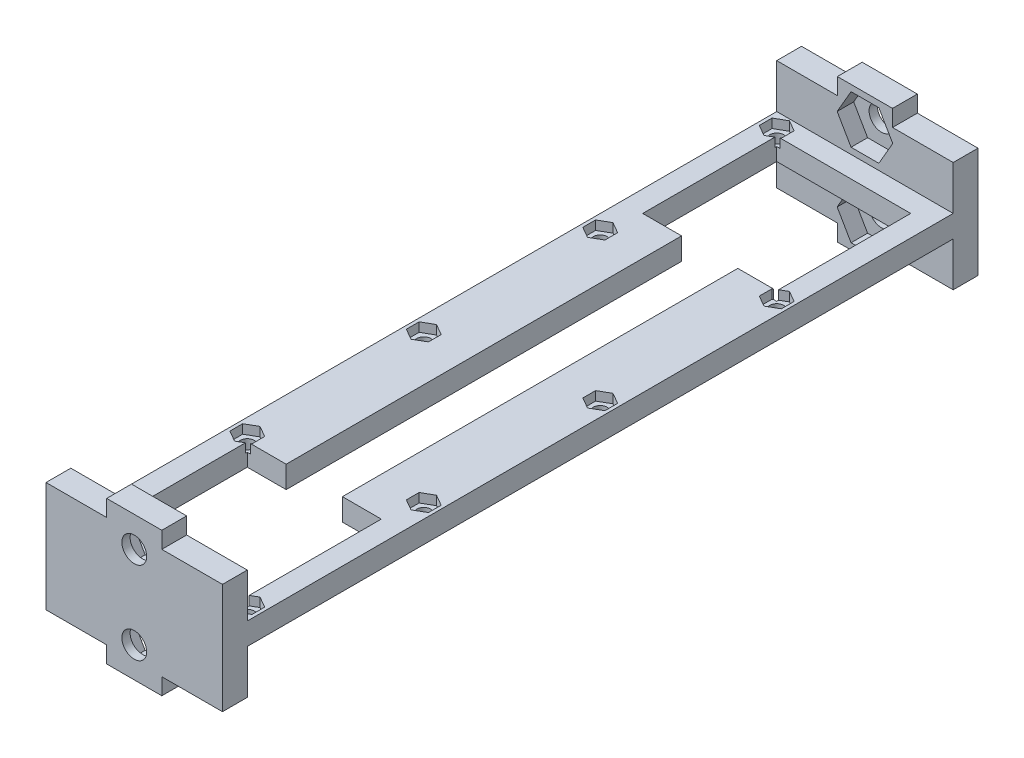
SolidWorks part; units mm, degrees
ref_plane "Front Plane" through (0, 0, 0) normal (0, 0, 1) x (1, 0, 0)
ref_plane "Top Plane" through (0, 0, 0) normal (0, 1, 0) x (1, 0, 0)
ref_plane "Right Plane" through (0, 0, 0) normal (1, 0, 0) x (0, 0, -1)
sketch "Sketch1" plane through (0, 0, 0) normal (0, 1, 0) x (1, 0, 0)
  line L1 (16, 64) -> (-16, 64)
  line L2 (16, 64) -> (16, -64)
  line L3 (16, -64) -> (-16, -64)
  line L4 (-16, 64) -> (-16, -64)
  line L5 (16, 64) -> (-16, -64) construction
  line L6 (16, -64) -> (-16, 64) construction
  point P0 (0, 0)
  dimension "D1" = 32
  dimension "D2" = 128
extrude "Boss-Extrude1" add sketch "Sketch1" along normal blind 4
sketch "Sketch4" plane through (0, 0, 0) normal (0, -1, 0) x (1, 0, 0)
  line L0 (-16, 64) -> (16, 64) construction
  line L1 (16, 64) -> (16, -64) construction
  circle A0 centre (13.4, 61.4) radius 1.25
  dimension "D1" = 2.5
  dimension "D2" = 2.6
  dimension "D3" = 2.6
extrude "Cut-Extrude2" cut sketch "Sketch4" against normal blind 10
sketch "Sketch5" plane through (0, 0, 0) normal (0, -1, 0) x (1, 0, 0)
  line L1 (16, -64) -> (-16, -64) construction
  line L2 (-16, -64) -> (-16, 64) construction
  circle A0 centre (-13.4, -61.4) radius 1.25
  dimension "D1" = 2.5
  dimension "D2" = 2.6
  dimension "D3" = 2.6
extrude "Cut-Extrude3" cut sketch "Sketch5" against normal blind 10
sketch "Sketch6" plane through (0, 4, 0) normal (0, 1, 0) x (1, 0, 0)
  line L0 (-15.4005, 62.555) -> (-13.4, 63.71)
  line L1 (-13.4, 63.71) -> (-11.3995, 62.555)
  line L2 (-11.3995, 62.555) -> (-11.3995, 60.245)
  line L3 (-11.3995, 60.245) -> (-13.4, 59.09)
  line L4 (-13.4, 59.09) -> (-15.4005, 60.245)
  line L5 (-15.4005, 60.245) -> (-15.4005, 62.555)
  line L6 (-13.4, 63.71) -> (-13.4, 59.09) construction
  point P4 (-13.4, 61.4)
  point P7 (-13.4, 61.4)
  dimension "D1" = 2.31
  dimension "D2" = 120
  dimension "D3" = 120
extrude "Cut-Extrude4" cut sketch "Sketch6" against normal blind 1.65
pattern_linear "LPattern3" count 4 spacing 32 along (0, 0, 1) of "Cut-Extrude3", "Cut-Extrude4"
sketch "Sketch7" plane through (0, 4, 0) normal (0, 1, 0) x (1, 0, 0)
  line L0 (13.4, -59.09) -> (11.3995, -60.245)
  line L1 (11.3995, -60.245) -> (11.3995, -62.555)
  line L2 (11.3995, -62.555) -> (13.4, -63.71)
  line L3 (13.4, -63.71) -> (15.4005, -62.555)
  line L4 (15.4005, -62.555) -> (15.4005, -60.245)
  line L5 (15.4005, -60.245) -> (13.4, -59.09)
  line L6 (13.4, -59.09) -> (13.4, -63.71) construction
  point P0 (13.4, -61.4)
  point P8 (13.4, -61.4)
  dimension "D1" = 120
  dimension "D2" = 120
  dimension "D3" = 2.31
extrude "Cut-Extrude5" cut sketch "Sketch7" against normal blind 1.65
pattern_linear "LPattern4" count 4 spacing 32 along (0, 0, -1) of "Cut-Extrude5", "Cut-Extrude2"
sketch "Sketch8" plane through (0, 0, 0) normal (0, -1, 0) x (1, 0, 0)
  line L0 (12.15, 61.4) -> (12.15, 31.9812) construction
  line L1 (13.4, 60.15) -> (-14.2218, 60.15) construction
  line L2 (-13.4, 35.85) -> (12.15, 35.85) construction
  line L4 (-12.15, 60.15) -> (12.15, 60.15)
  line L5 (-12.15, 34.6) -> (-12.15, 60.15) construction
  line L6 (-12.15, 60.15) -> (-12.15, 35.85)
  line L7 (-12.15, 35.85) -> (12.15, 35.85)
  line L8 (12.15, 60.15) -> (12.15, 35.85)
  circle A2 centre (13.4, 61.4) radius 1.25 construction
  circle A3 centre (-13.4, 34.6) radius 1.25 construction
extrude "Cut-Extrude6" cut sketch "Sketch8" against normal blind 10
mirror "Mirror1" about plane through (0, 0, 0) normal (0, 0, 1) of "Cut-Extrude6"
sketch "Sketch9" plane through (0, 0, -64) normal (0, 0, -1) x (-1, 0, 0)
  line L0 (0, 0) -> (0, 4) construction
  line L1 (-16, 0) -> (16, 0) construction
  line L2 (-16, 4) -> (16, 4) construction
  line L3 (-16, 2) -> (16, 2) construction
  line L4 (-16, 4) -> (-16, 0) construction
  line L5 (16, 4) -> (16, 0) construction
  line L6 (-16, 12) -> (-5, 12)
  line L8 (16, -8) -> (16, 12)
  line L10 (-16, -8) -> (-16, 12)
  line L11 (16, -8) -> (-16, 12) construction
  line L12 (16, 12) -> (-16, -8) construction
  line L13 (-5, 12) -> (-5, 15)
  line L14 (-5, 15) -> (5, 15)
  line L15 (5, 15) -> (5, 12)
  line L16 (5, 12) -> (16, 12)
  line L17 (-16, -8) -> (-5, -8)
  line L18 (-5, -8) -> (-5, -11)
  line L19 (-5, -11) -> (5, -11)
  line L20 (5, -11) -> (5, -8)
  line L21 (5, -8) -> (16, -8)
  point P12 (0, 2)
  dimension "D1" = 32
  dimension "D2" = 20
  dimension "D3" = 10
  dimension "D4" = 3
  dimension "D5" = 3
extrude "Boss-Extrude2" add sketch "Sketch9" along normal blind 4.5
sketch "Sketch11" plane through (0, 0, 0) normal (0, -1, 0) x (1, 0, 0)
  line L0 (-5.1, 35.85) -> (-5.1, -35.85)
  line L1 (-12.15, 35.85) -> (12.15, 35.85) construction
  line L2 (-12.15, -35.85) -> (12.15, -35.85) construction
  line L3 (-5.1, -35.85) -> (5.1, -35.85)
  line L4 (5.1, -35.85) -> (5.1, 35.85)
  line L5 (5.1, 35.85) -> (-5.1, 35.85)
  point P6 (0, 35.85)
  dimension "D1" = 10.2
extrude "Cut-Extrude7" cut sketch "Sketch11" against normal through all
sketch "Sketch10" plane through (0, 0, -64) normal (0, 0, 1) x (1, 0, 0)
  line L0 (-2.52, 13.8648) -> (2.52, 13.8648)
  line L1 (2.52, 13.8648) -> (5.04, 9.5)
  line L2 (5.04, 9.5) -> (2.52, 5.1352)
  line L3 (2.52, 5.1352) -> (-2.52, 5.1352)
  line L4 (-2.52, 5.1352) -> (-5.04, 9.5)
  line L5 (-5.04, 9.5) -> (-2.52, 13.8648)
  line L6 (-5.04, 9.5) -> (5.04, 9.5) construction
  line L7 (0, 13.8648) -> (0, 4.395) construction
  line L14 (-16, 2) -> (16, 2) construction
  line L15 (-16, 4) -> (-16, 0) construction
  line L16 (16, 4) -> (16, 0) construction
  point P7 (0, 2)
  point P8 (0, 5.1352)
  point P11 (0, 9.5)
  dimension "D1" = 120
  dimension "D2" = 120
  dimension "D3" = 5.04
  dimension "D4" = 7.5
extrude "Cut-Extrude8" cut sketch "Sketch10" against normal blind 3
sketch "Sketch12" plane through (0, 0, -67) normal (0, 0, 1) x (1, 0, 0)
  line L0 (-5.04, 9.5) -> (5.04, 9.5) construction
  circle A0 centre (0, 9.5) radius 2.25
  point P6 (0, 9.5)
  dimension "D1" = 4.5
extrude "Cut-Extrude9" cut sketch "Sketch12" against normal blind 3
ref_plane "midplane" through (0, 2, 0) normal (0, 1, 0) x (1, 0, 0)
mirror "Mirror2" about plane through (0, 2, 0) normal (0, 1, 0) of "Cut-Extrude9", "Cut-Extrude8"
mirror "Mirror3" about plane through (0, 0, 0) normal (0, 0, 1) of "Cut-Extrude8", "Cut-Extrude9", "Mirror2", "Boss-Extrude2"
